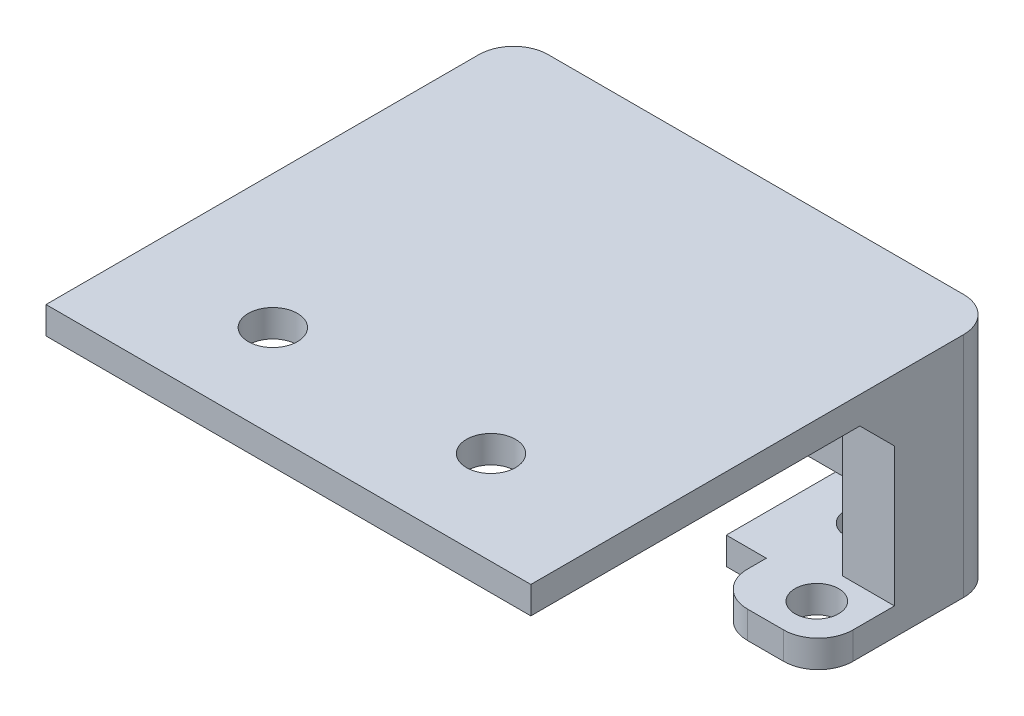
SolidWorks part; units mm, degrees
ref_plane "Front Plane" through (0, 0, 0) normal (0, 0, 1) x (1, 0, 0)
ref_plane "Top Plane" through (0, 0, 0) normal (0, 1, 0) x (1, 0, 0)
ref_plane "Right Plane" through (0, 0, 0) normal (1, 0, 0) x (0, 0, -1)
sketch "Sketch2" plane through (0, 84.355, 0) normal (0, 1, 0) x (1, 0, 0)
  line L0 (86.1651, -169.9402) -> (88.8151, -169.9402)
  line L1 (113.9951, -169.9402) -> (116.6451, -169.9402)
  line L2 (91.3551, -166.4322) -> (91.3551, -166.0202) construction
  line L3 (111.4551, -166.4322) -> (111.4551, -166.0202) construction
  line L4 (94.2931, -156.7322) -> (94.2931, -163.0822)
  line L5 (108.5171, -156.7322) -> (108.5171, -163.0822)
  line L6 (94.2931, -156.7322) -> (86.1651, -156.7322)
  line L7 (91.3551, -166.0202) -> (94.2931, -166.0202)
  line L8 (91.3551, -176.8772) -> (91.3551, -166.4322)
  line L9 (91.3551, -166.4322) -> (111.4551, -166.4322)
  line L10 (111.4551, -166.4322) -> (111.4551, -176.8772)
  line L11 (113.9951, -179.4172) -> (116.6451, -179.4172)
  line L12 (119.1851, -176.8772) -> (119.1851, -159.2722)
  line L13 (116.6451, -156.7322) -> (86.1651, -156.7322)
  line L14 (83.6251, -159.2722) -> (83.6251, -176.8772)
  line L15 (86.1651, -179.4172) -> (88.8151, -179.4172)
  line L16 (91.3551, -167.4002) -> (91.3551, -166.0202)
  line L18 (111.4551, -166.0202) -> (111.4551, -167.4002)
  line L20 (119.1851, -167.4002) -> (119.1851, -159.2722)
  line L21 (116.6451, -156.7322) -> (108.5171, -156.7322)
  line L22 (83.6251, -159.2722) -> (83.6251, -167.4002)
  line L23 (94.2931, -166.0202) -> (94.2931, -163.0822)
  line L24 (108.5171, -163.0822) -> (108.5171, -166.0202)
  line L25 (108.5171, -166.0202) -> (111.4551, -166.0202)
  line L26 (91.3551, -166.0202) -> (91.3551, -166.4322) construction
  line L27 (111.4551, -166.4322) -> (111.4551, -166.0202) construction
  arc A0 (116.6451, -169.9402) -> (119.1851, -167.4002) centre (116.6451, -167.4002) ccw
  arc A1 (113.9951, -169.9402) -> (111.4551, -167.4002) centre (113.9951, -167.4002) cw
  arc A2 (88.8151, -169.9402) -> (91.3551, -167.4002) centre (88.8151, -167.4002) ccw
  arc A3 (86.1651, -169.9402) -> (83.6251, -167.4002) centre (86.1651, -167.4002) cw
  circle A4 centre (116.0369, -166.899) radius 1.6 construction
  circle A5 centre (112.9147, -160.0901) radius 1.6 construction
  arc A6 (111.4551, -176.8772) -> (113.9951, -179.4172) centre (113.9951, -176.8772) ccw
  arc A7 (116.6451, -179.4172) -> (119.1851, -176.8772) centre (116.6451, -176.8772) ccw
  arc A8 (119.1851, -159.2722) -> (116.6451, -156.7322) centre (116.6451, -159.2722) ccw
  arc A9 (86.1651, -156.7322) -> (83.6251, -159.2722) centre (86.1651, -159.2722) ccw
  arc A10 (83.6251, -176.8772) -> (86.1651, -179.4172) centre (86.1651, -176.8772) ccw
  arc A11 (88.8151, -179.4172) -> (91.3551, -176.8772) centre (88.8151, -176.8772) ccw
  arc A14 (119.1851, -159.2722) -> (116.6451, -156.7322) centre (116.6451, -159.2722) ccw
  arc A15 (86.1651, -156.7322) -> (83.6251, -159.2722) centre (86.1651, -159.2722) ccw
  circle A18 centre (86.7734, -166.899) radius 1.6 construction
  circle A19 centre (89.8955, -160.0901) radius 1.6 construction
  circle A20 centre (116.0369, -166.899) radius 1.6
  circle A21 centre (112.9147, -160.0901) radius 1.6
  circle A22 centre (86.7734, -166.899) radius 1.6
  circle A23 centre (89.8955, -160.0901) radius 1.6
  arc A24 (94.2931, -163.0822) -> (91.3551, -166.0202) centre (91.3551, -163.0822) cw construction
  arc A25 (108.5171, -163.0822) -> (111.4551, -166.0202) centre (111.4551, -163.0822) ccw construction
  point P29 (91.3551, -169.9402)
  dimension "D3" = 2.54
  dimension "D4" = 10.668
  dimension "D6" = 6.35
  dimension "D2" = 13.208
  dimension "D5" = 10.668
  dimension "D1" = 0
extrude "Boss-Extrude1" add sketch "Sketch2" along normal blind 2 contours L16 L7 L23 L4 L6 A15 L22 A3 L0 A2 | L18 A1 L1 A0 L20 A14 L21 L5 L24 L25 | A23 | A22 | A21 | A20
sketch "Sketch3" plane through (0, 86.355, 0) normal (0, 1, 0) x (1, 0, 0)
  line L3 (119.1851, -167.4002) -> (119.1851, -159.2722) construction
  line L4 (116.6451, -156.7322) -> (86.1651, -156.7322) construction
  line L5 (94.2931, -156.7322) -> (86.1651, -156.7322) construction
  line L6 (83.6251, -159.2722) -> (83.6251, -167.4002) construction
  line L7 (119.1851, -164.3522) -> (119.1851, -159.2722)
  line L8 (116.6451, -156.7322) -> (86.1651, -156.7322)
  line L9 (94.2931, -156.7322) -> (86.1651, -156.7322)
  line L10 (83.6251, -159.2722) -> (83.6251, -164.3522)
  line L11 (83.6251, -164.3522) -> (87.4351, -164.3522)
  line L12 (87.4351, -164.3522) -> (87.4351, -158.0022)
  line L13 (87.4351, -158.0022) -> (115.3751, -158.0022)
  line L14 (115.3751, -158.0022) -> (115.3751, -164.3522)
  line L15 (115.3751, -164.3522) -> (119.1851, -164.3522)
  arc A4 (119.1851, -159.2722) -> (116.6451, -156.7322) centre (116.6451, -159.2722) ccw construction
  arc A5 (86.1651, -156.7322) -> (83.6251, -159.2722) centre (86.1651, -159.2722) ccw construction
  arc A6 (119.1851, -159.2722) -> (116.6451, -156.7322) centre (116.6451, -159.2722) ccw
  arc A7 (86.1651, -156.7322) -> (83.6251, -159.2722) centre (86.1651, -159.2722) ccw
  point P11 (101.4051, -158.0022)
  point P16 (101.4051, -156.7322)
  line M10 (119.1851, -167.4002) -> (119.1851, -159.2722)
  arc M11 (119.1851, -159.2722) -> (116.6451, -156.7322) centre (116.6451, -159.2722) ccw
  line M12 (116.6451, -156.7322) -> (108.5171, -156.7322)
  line M13 (108.5171, -156.7322) -> (108.5171, -166.0202)
  dimension "D1" = 1.27
  dimension "D2" = 7.62
  dimension "D3" = 27.94
extrude "Boss-Extrude2" add sketch "Sketch3" along normal blind 12.7 contours L8 A7 L10 L11 L12 L13 M13 | L14 L15 L13 M10 M11 M12 M13
sketch "Sketch4" plane through (0, 99.055, 0) normal (0, 1, 0) x (1, 0, 0)
  line L0 (83.6251, -164.3522) -> (83.6251, -191.0222)
  line L1 (83.6251, -191.0222) -> (119.1851, -191.0222)
  line L2 (119.1851, -191.0222) -> (119.1851, -164.3522)
  line L3 (93.4051, -184.1642) -> (109.4051, -184.1642) construction
  line L8 (116.6451, -156.7322) -> (86.1651, -156.7322)
  line L9 (83.6251, -159.2722) -> (83.6251, -164.3522)
  line L10 (83.6251, -164.3522) -> (87.4351, -164.3522)
  line L11 (87.4351, -164.3522) -> (87.4351, -158.0022)
  line L12 (87.4351, -158.0022) -> (115.3751, -158.0022)
  line L13 (115.3751, -158.0022) -> (115.3751, -164.3522)
  line L14 (115.3751, -164.3522) -> (119.1851, -164.3522)
  line L15 (119.1851, -164.3522) -> (119.1851, -159.2722)
  line L16 (116.6451, -156.7322) -> (86.1651, -156.7322)
  line L17 (83.6251, -159.2722) -> (83.6251, -164.3522)
  line L23 (119.1851, -164.3522) -> (119.1851, -159.2722)
  circle A0 centre (93.4051, -184.1642) radius 1.8
  circle A1 centre (109.4051, -184.1642) radius 1.8
  arc A2 (86.1651, -156.7322) -> (83.6251, -159.2722) centre (86.1651, -159.2722) ccw
  arc A3 (119.1851, -159.2722) -> (116.6451, -156.7322) centre (116.6451, -159.2722) ccw
  arc A4 (86.1651, -156.7322) -> (83.6251, -159.2722) centre (86.1651, -159.2722) ccw
  arc A5 (119.1851, -159.2722) -> (116.6451, -156.7322) centre (116.6451, -159.2722) ccw
  point P17 (101.4051, -184.1642)
  point P20 (101.4051, -156.7322)
  dimension "D3" = 3.6
  dimension "D2" = 34.29
  dimension "D4" = 27.432
  dimension "D5" = 16
  dimension "D1" = 0
extrude "Boss-Extrude3" add sketch "Sketch4" along normal blind 2
chamfer "Chamfer1" distance 2.54 angle 45 5 edges at (117.2801, 99.055, 164.3522) (115.3751, 99.055, 161.1772) (85.5301, 99.055, 164.3522) (87.4351, 99.055, 161.1772) (101.4051, 99.055, 158.0022)
